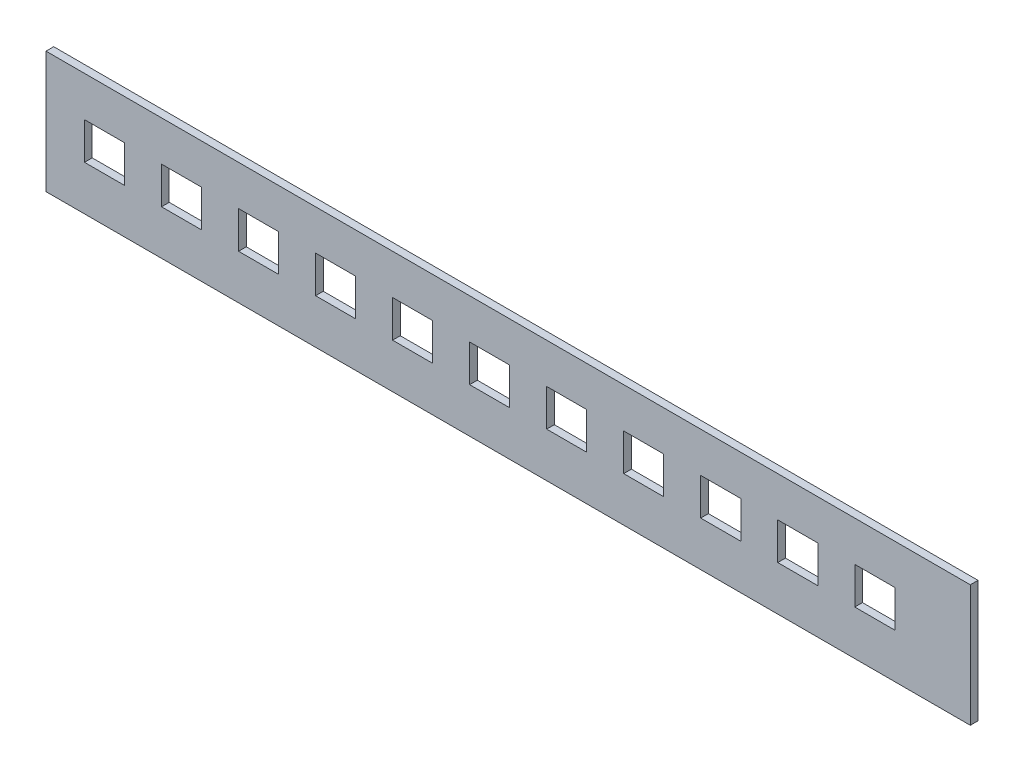
SolidWorks part; units mm, degrees
ref_plane "Front Plane" through (0, 0, 0) normal (0, 0, 1) x (1, 0, 0)
ref_plane "Top Plane" through (0, 0, 0) normal (0, 1, 0) x (1, 0, 0)
ref_plane "Right Plane" through (0, 0, 0) normal (1, 0, 0) x (0, 0, -1)
sketch "Sketch1" plane through (0, 0, 0) normal (0, 0, 1) x (1, 0, 0)
  line L1 (0, 0) -> (60, 0)
  line L2 (0, 0) -> (0, -7.9)
  line L3 (0, -7.9) -> (60, -7.9)
  line L4 (60, 0) -> (60, -7.9)
extrude "Boss-Extrude1" add sketch "Sketch1" along normal blind 0.5 contours L3 L4 L1 L2
sketch "Sketch2" plane through (0, 0, 0.5) normal (0, 0, 1) x (1, 0, 0)
  line L1 (2.5, -2.6) -> (5.1, -2.6)
  line L2 (2.5, -2.6) -> (2.5, -5)
  line L3 (2.5, -5) -> (5.1, -5)
  line L4 (5.1, -2.6) -> (5.1, -5)
  point P4 (0, 0)
  point P5 (0, 0)
  point P6 (0, 0)
  point P7 (0, 0)
  point P8 (0, 0)
  point P9 (0, 0)
  point P10 (0, 0)
  point P11 (0, 0)
  point P12 (0, 0)
  point P13 (0, 0)
  point P14 (0, 0)
extrude "Cut-Extrude1" cut sketch "Sketch2" against normal through all both and the other way through all contours L3 L4 L1 L2
pattern_linear "LPattern1" count 11 spacing 5 along (1, 0, 0) of "Cut-Extrude1"
